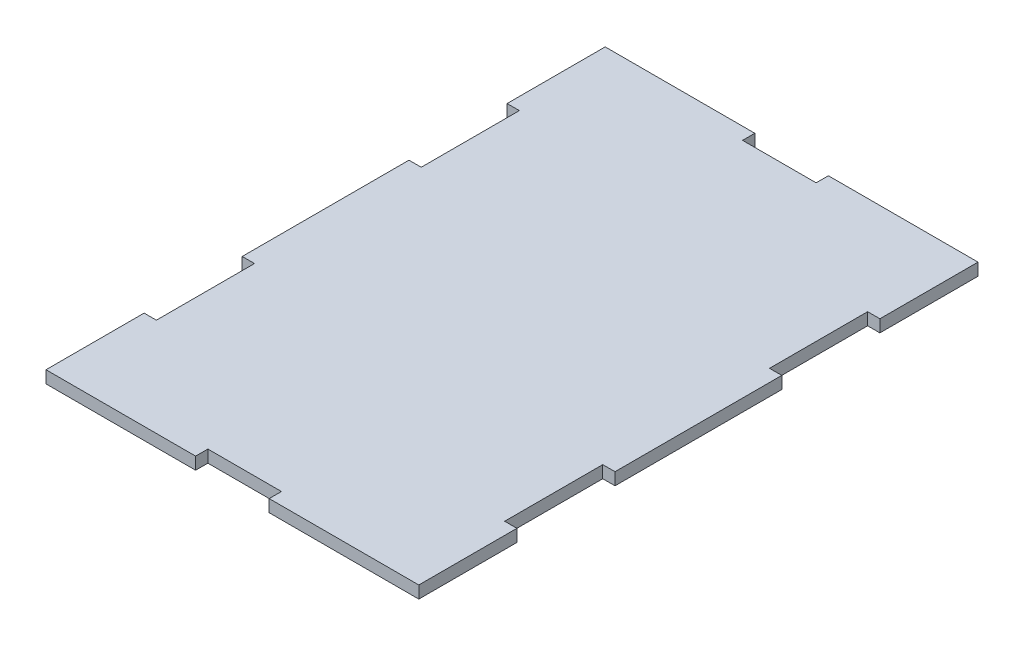
SolidWorks part; units mm, degrees
ref_plane "Front Plane" through (0, 0, 0) normal (0, 0, 1) x (1, 0, 0)
ref_plane "Top Plane" through (0, 0, 0) normal (0, 1, 0) x (1, 0, 0)
ref_plane "Right Plane" through (0, 0, 0) normal (1, 0, 0) x (0, 0, -1)
sketch "Sketch1" plane through (0, 0, 0) normal (0, 1, 0) x (1, 0, 0)
  line L0 (38.735, 144.78) -> (38.735, 141.605)
  line L1 (0, 0) -> (38.735, 0)
  line L2 (0, 0) -> (0, 25.4)
  line L3 (0, 144.78) -> (38.735, 144.78)
  line L4 (96.52, 0) -> (96.52, 25.4)
  line L5 (38.735, 141.605) -> (57.785, 141.605)
  line L6 (57.785, 141.605) -> (57.785, 144.78)
  line L7 (57.785, 144.78) -> (96.52, 144.78)
  line L8 (48.26, 3.175) -> (48.26, 159.7274) construction
  line L9 (0, 119.38) -> (3.175, 119.38)
  line L10 (3.175, 119.38) -> (3.175, 93.98)
  line L11 (3.175, 93.98) -> (0, 93.98)
  line L12 (0, 72.39) -> (96.52, 72.39) construction
  line L13 (0, 119.38) -> (0, 144.78)
  line L14 (3.175, 50.8) -> (0, 50.8)
  line L15 (3.175, 25.4) -> (3.175, 50.8)
  line L16 (0, 25.4) -> (3.175, 25.4)
  line L17 (0, 50.8) -> (0, 93.98)
  line L18 (96.52, 25.4) -> (93.345, 25.4)
  line L19 (93.345, 25.4) -> (93.345, 50.8)
  line L20 (93.345, 50.8) -> (96.52, 50.8)
  line L21 (93.345, 93.98) -> (96.52, 93.98)
  line L22 (93.345, 119.38) -> (93.345, 93.98)
  line L23 (96.52, 119.38) -> (93.345, 119.38)
  line L24 (96.52, 119.38) -> (96.52, 144.78)
  line L25 (96.52, 50.8) -> (96.52, 93.98)
  line L26 (38.735, 0) -> (38.735, 3.175)
  line L27 (38.735, 3.175) -> (57.785, 3.175)
  line L28 (57.785, 3.175) -> (57.785, 0)
  line L29 (57.785, 0) -> (96.52, 0)
  point P11 (48.26, 141.605)
  dimension "D1" = 144.78
  dimension "D2" = 96.52
  dimension "D3" = 19.05
  dimension "D4" = 3.175
  dimension "D5" = 25.4
  dimension "D6" = 25.4
  dimension "D7" = 3.175
extrude "Boss-Extrude1" add sketch "Sketch1" along normal blind 3.175
